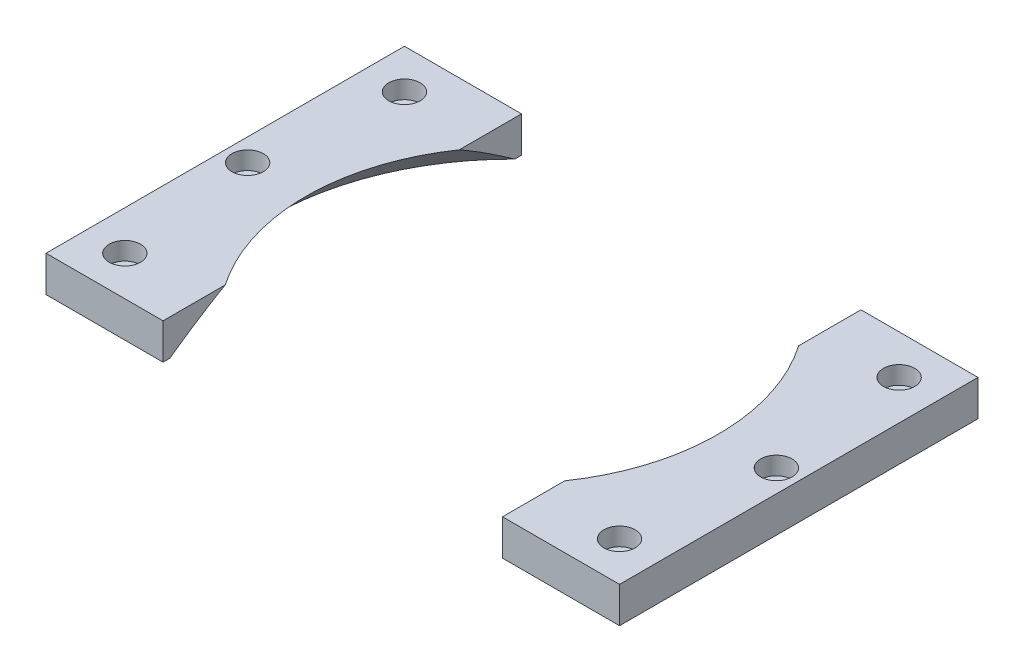
SolidWorks part; units mm, degrees
material "Malleable Cast Iron"
ref_plane "Front Plane" through (0, 0, 0) normal (0, 0, 1) x (1, 0, 0)
ref_plane "Top Plane" through (0, 0, 0) normal (0, 1, 0) x (1, 0, 0)
ref_plane "Right Plane" through (0, 0, 0) normal (1, 0, 0) x (0, 0, -1)
sketch "Sketch1" plane through (0, 0, 0) normal (0, 1, 0) x (1, 0, 0)
  line L0 (-101.6, 0) -> (101.6, 0) construction
  line L1 (-101.6, -63.5) -> (101.6, -63.5) construction
  line L2 (-101.6, -63.5) -> (-101.6, 63.5)
  line L3 (-101.6, 63.5) -> (101.6, 63.5) construction
  line L4 (101.6, -63.5) -> (101.6, 63.5)
  line L5 (0, 63.5) -> (0, -63.5) construction
  line L6 (57.5893, 63.5) -> (101.6, 63.5)
  line L7 (57.5893, -63.5) -> (101.6, -63.5)
  line L8 (-101.6, -63.5) -> (-57.5893, -63.5)
  line L9 (-101.6, 63.5) -> (-57.5893, 63.5)
  arc A0 (-57.5893, 63.5) -> (-57.5893, -63.5) centre (0, 0) ccw
  arc A1 (57.5893, -63.5) -> (57.5893, 63.5) centre (0, 0) ccw
  dimension "D3" = 171.45
  dimension "D1" = 203.2
  dimension "D2" = 127
extrude "Boss-Extrude1" add sketch "Sketch1" along normal blind 12.7
draft "Draft1" type of draft neutral plane draft angle 45 faces to draft 1 face at (71.6571, 6.35, 0) neutral plane through (0, 0, 0) neutral plane normal (0, -1, 0) parameters "D1"=45
draft "Draft2" type of draft neutral plane draft angle 45 faces to draft 1 face at (-71.6571, 6.35, 0) neutral plane through (0, 0, 0) neutral plane normal (0, -1, 0) parameters "D1"=45
sketch "Sketch2" plane through (0, 0, 0) normal (0, -1, 0) x (1, 0, 0)
  line L0 (-101.6, 63.5) -> (-57.5893, 63.5) construction
  line L1 (-60.1293, 63.5) -> (60.1293, 63.5)
  line L2 (-60.1293, 63.5) -> (-60.1293, -63.5)
  line L3 (-60.1293, -63.5) -> (60.1293, -63.5)
  line L4 (60.1293, 63.5) -> (60.1293, -63.5)
  line L5 (101.6, -63.5) -> (57.5893, -63.5) construction
  dimension "D1" = 2.54
  dimension "D2" = 2.54
extrude "Cut-Extrude1" cut sketch "Sketch2" against normal through all
hole_wizard "CBORE for 1/4 Socket Head Cap Screw1" positions "Sketch3" profile "Sketch4" counterbore size "1/4" standard "ANSI Inch" end condition through all
sketch "Sketch3" plane through (-101.6, 12.7, 63.5) normal (0, 1, 0) x (1, 0, 0)
  line L0 (189.23, 113.03) -> (189.23, 13.97) construction
  line L1 (187.325, 63.5) -> (203.2, 63.5) construction
  line L4 (41.4707, 127) -> (161.7293, 127) construction
  line L5 (101.6, 127) -> (101.6, 0) construction
  arc A1 (161.7293, 2.3997) -> (161.7293, 124.6003) centre (101.6, 63.5) ccw construction
  point P0 (189.23, 13.97)
  point P2 (195.2625, 63.5)
  point P4 (189.23, 113.03)
  point P30 (13.97, 113.03)
  point P31 (7.9375, 63.5)
  point P32 (13.97, 13.97)
sketch "Sketch4" plane through (87.63, 12.7, 49.53) normal (1, 0, 0) x (0, 0, 1)
  line L0 (0, 0) -> (0, 12.7)
  line L1 (0, 12.7) -> (3.3782, 12.7)
  line L3 (3.3782, 12.7) -> (3.3782, 6.35)
  line L4 (3.3782, 6.35) -> (5.5562, 6.35)
  line L5 (5.5562, 6.35) -> (5.5562, 0)
  line L7 (5.5562, 0) -> (0, 0)
  line L11 (0, -6.35) -> (0, 107.95) construction
  dimension "Thru Hole Dia." = 6.7564
  dimension "Thru Hole Depth" = 12.7
  dimension "C'Bore Dia." = 11.1125
  dimension "C'Bore Depth" = 6.35
equation "\"delta-z\" = 1.5"
equation "\"total-height\" = 3.28"
equation "\"mid-height\" = 1.5"
equation "\"jaw-width\" = 4"
equation "\"jaw-height\" = \"total-height\" - \"mid-height\""
equation "\"max-tube-diam\" = 3.5"
equation "\"v-block-notch-height\" = 1.5"
equation "\"v-block-notch-angle\" = 120"
equation "\"vise-mod-plate-thickness\"= .375"
equation "\"vise-mod-height\"= .5 * \"max-tube-diam\" + \"delta-z\""
equation "\"jaw-travel\" = 4.45"
equation "\"rib-top-width\" = 0.5"
equation "\"rib-side-width\" = 0.5"
equation "\"quarter-twenty-close-clearance\" = .257"
equation "\"box-way-width\" = 1.5"
equation "\"box-way-depth\" = 1.5"
equation "\"screw-OD\" = .625"
equation "\"screw-reduced-diam\" = .47"
equation "\"pressure-plate-OD\" = 6.75"
equation "\"swivel-cleat-thick\" = .5"
equation "\"swivel-gap\" = .02"
equation "\"D3@Sketch1\"=\"pressure-plate-OD\""
equation "\"D1@Boss-Extrude1\"=\"swivel-cleat-thick\""
